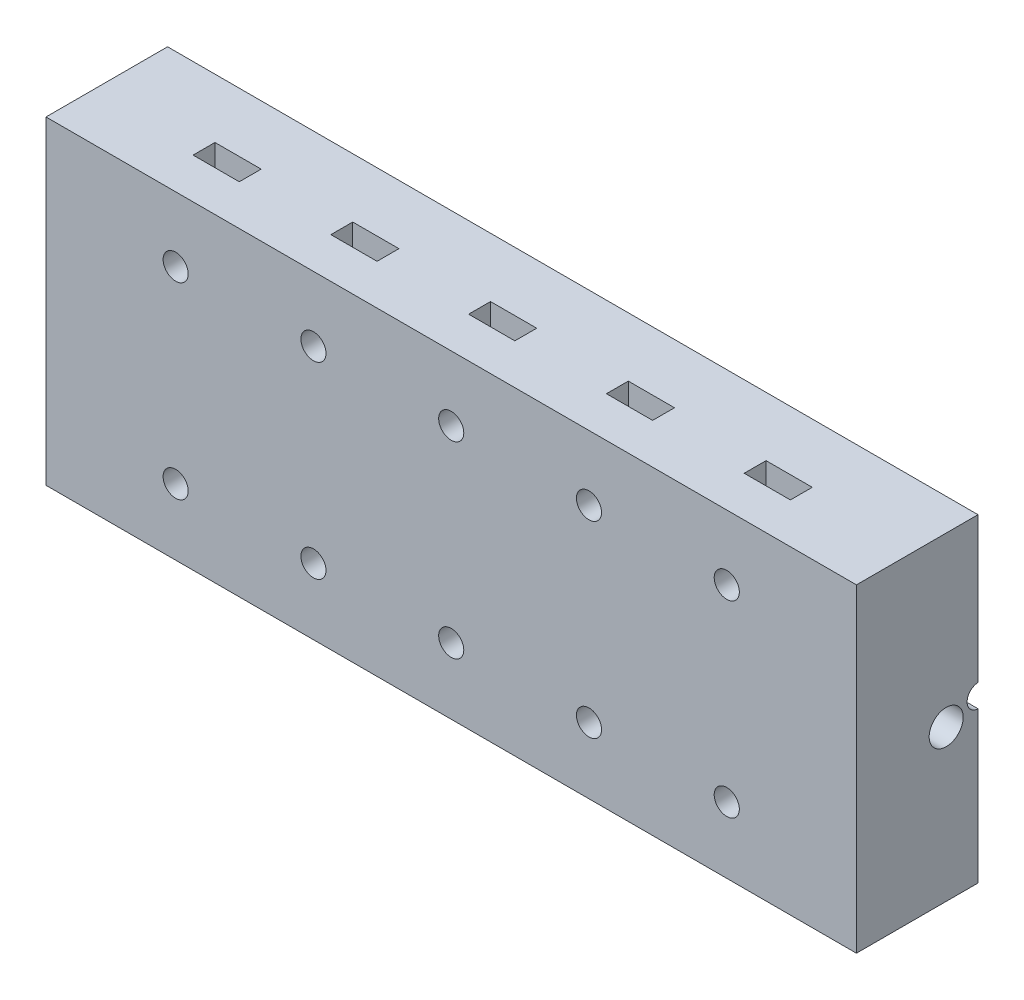
SolidWorks part; units mm, degrees
ref_plane "Ebene vorne" through (0, 0, 0) normal (0, 0, 1) x (1, 0, 0)
ref_plane "Ebene oben" through (0, 0, 0) normal (0, 1, 0) x (1, 0, 0)
ref_plane "Ebene rechts" through (0, 0, 0) normal (1, 0, 0) x (0, 0, -1)
sketch "Skizze2" plane through (0, 0, 0) normal (0, 0, 1) x (1, 0, 0)
  line L1 (0, 0) -> (100, 0)
  line L2 (0, 0) -> (0, 39.3642)
  line L3 (0, 39.3642) -> (100, 39.3642)
  line L4 (100, 0) -> (100, 39.3642)
  dimension "D1" = 39.3642
  dimension "D2" = 100
extrude "Aufsatz-Linear austragen1" add sketch "Skizze2" along normal blind 30
sketch "Skizze3" plane through (0, 0, 30) normal (0, 0, 1) x (1, 0, 0)
  line L0 (0, 19.6821) -> (100, 19.6821) construction
  line L1 (0, 39.3642) -> (0, 0) construction
  line L2 (100, 0) -> (100, 39.3642) construction
ref_plane "Ebene2" through (0, 19.7642, 0) normal (0, 1, 0) x (1, 0, 0)
sketch "Skizze9" plane through (0, 0, 30) normal (0, 0, 1) x (1, 0, 0)
  line L0 (50, 0) -> (50, 39.3642) construction
  line L1 (0, 0) -> (100, 0) construction
  line L2 (100, 39.3642) -> (0, 39.3642) construction
ref_plane "Ebene3" through (50, 0, 0) normal (-1, 0, 0) x (0, 0, 1)
sketch "Skizze10" plane through (50, 0, 0) normal (-1, 0, 0) x (0, 0, 1)
  line L0 (14.9458, 42.0451) -> (14.9458, -1.991) construction
  line L1 (-1.6741, 19.9497) -> (31.3778, 19.9497) construction
  circle A0 centre (14.9458, 20.027) radius 5
  dimension "D1" = 10
extrude "Schnitt-Linear austragen1" cut sketch "Skizze10" against normal blind 40 and the other way blind 40
ref_plane "Ebene4" through (90, 0, 0) normal (-1, 0, 0) x (0, 0, 1)
ref_plane "Ebene5" through (10, 0, 0) normal (-1, 0, 0) x (0, 0, 1)
sketch "Skizze17" plane through (90, 0, 0) normal (-1, 0, 0) x (0, 0, 1)
  circle A0 centre (14.9458, 20.027) radius 1.4
  dimension "D1" = 2.8
extrude "Schnitt-Linear austragen2" cut sketch "Skizze17" against normal through all
mirror "Spiegeln1" about plane through (50, 0, 0) normal (-1, 0, 0) of "Schnitt-Linear austragen2"
sketch "Skizze18" plane through (0, 39.3642, 0) normal (0, 1, 0) x (1, 0, 0)
  line L0 (100, -15) -> (0, -15) construction
  line L1 (100, -30) -> (100, 0) construction
ref_plane "Ebene6" through (0, 0, 15) normal (0, 0, -1) x (-1, 0, 0)
sketch "Skizze24" plane through (0, 0, 30) normal (0, 0, 1) x (1, 0, 0)
  line L0 (0, 39.3642) -> (0, 0) construction
  line L1 (100, 39.3642) -> (0, 39.3642) construction
  line L4 (100, 0) -> (100, 39.3642) construction
  circle A0 centre (16, 31.3642) radius 1.55
  circle A1 centre (33, 31.3642) radius 1.55
  circle A2 centre (50, 31.3642) radius 1.55
  circle A3 centre (67, 31.3642) radius 1.55
  circle A4 centre (84, 31.3642) radius 1.55
  dimension "D1" = 3.1
  dimension "D4" = 3.1
  dimension "D5" = 3.1
  dimension "D6" = 3.1
  dimension "D7" = 3.1
  dimension "D2" = 16
  dimension "D3" = 8
  dimension "D8" = 17
  dimension "D9" = 17
  dimension "D10" = 17
  dimension "D11" = 17
  dimension "D12" = 16
extrude "Schnitt-Linear austragen4" cut sketch "Skizze24" against normal through all
sketch "Skizze22" plane through (0, 0, 0) normal (-1, 0, 0) x (0, 0, 1)
  line L0 (30, 39.3642) -> (0, 39.3642) construction
  line L1 (0, 0) -> (15, 0)
  line L2 (0, 0) -> (0, 39.3642)
  line L3 (0, 39.3642) -> (15, 39.3642)
ref_plane "Ebene7" through (0, 0, 8.4) normal (0, 0, -1) x (-1, 0, 0)
ref_plane "Ebene8" through (16, 0, 0) normal (-1, 0, 0) x (0, 0, 1)
sketch "Skizze35" plane through (0, 0, 30) normal (0, 0, 1) x (1, 0, 0)
  line L0 (89.9018, 21.3451) -> (89.9018, 39.3769) construction
  line L1 (89.9018, 39.3769) -> (89.9018, 0) construction
  line L2 (0, 0) -> (100, 0) construction
ref_plane "Ebene9" through (90, 0, 0) normal (1, 0, 0) x (0, 0, -1)
sketch "Skizze36" plane through (90, 0, 0) normal (1, 0, 0) x (0, 0, -1)
  line L0 (-20.1004, 18.2046) -> (-18.9246, 18.6336)
  circle A0 centre (-18.9246, 18.6336) radius 0.75
  point P3 (-19.5125, 18.4191)
  dimension "D1" = 1.5
sketch "Skizze37" plane through (100, 0, 0) normal (1, 0, 0) x (0, 0, -1)
  circle A0 centre (-18.9246, 18.6336) radius 0.7369
extrude "Schnitt-Linear austragen9" cut sketch "Skizze37" against normal through all
sketch "Skizze40" plane through (100, 0, 0) normal (1, 0, 0) x (0, 0, -1)
  circle A0 centre (-18.9246, 18.6336) radius 2.1
  dimension "D1" = 4.2
extrude "Schnitt-Linear austragen10" cut sketch "Skizze40" against normal blind 6
sketch "Skizze42" plane through (0, 0, 0) normal (-1, 0, 0) x (0, 0, 1)
  line L0 (10.1439, 18.6336) -> (10.8642, 18.8426) construction
  circle A0 centre (14.9458, 20.027) radius 5 construction
  circle A1 centre (10.8642, 18.8426) radius 0.75
  dimension "D1" = 0.75
extrude "Schnitt-Linear austragen12" cut sketch "Skizze42" against normal blind 10
fillet "Verrundung1" radius 1 1 edges at (94, 18.6336, 18.1877)
sketch "Skizze46" plane through (0, 0, 0) normal (0, 0, -1) x (-1, 0, 0)
  circle A0 centre (-84, 31.3642) radius 2.85
  dimension "D1" = 5.7
extrude "Schnitt-Linear austragen15" cut sketch "Skizze46" against normal blind 10
sketch "Skizze50" plane through (0, 0, 30) normal (0, 0, 1) x (1, 0, 0)
  line L0 (81.15, 33.0096) -> (81.15, 39.3642)
  line L2 (81.15, 33.0096) -> (81.15, 29.7187)
  line L3 (81.15, 29.7187) -> (84, 28.0733)
  line L4 (84, 28.0733) -> (86.85, 29.7187)
  line L5 (86.85, 29.7187) -> (86.85, 33.0096)
  line L7 (100, 39.3642) -> (0, 39.3642) construction
  line L8 (81.15, 39.3642) -> (86.85, 39.3642)
  line L9 (86.85, 39.3642) -> (86.85, 33.0096)
  line L11 (84, 34.6551) -> (81.15, 33.0096) [skipped]
  line L12 (86.85, 33.0096) -> (84, 34.6551) [skipped]
  circle A0 centre (84, 31.3642) radius 2.85 construction
  dimension "D1" = 5.7
extrude "Schnitt-Linear austragen25" cut sketch "Skizze50" against normal blind 2.7 from offset 5 offset against normal yes
pattern_linear "Lineares Muster1" count 5 spacing 17 along (-1, 0, 0) of "Schnitt-Linear austragen25", "Schnitt-Linear austragen15"
mirror "Spiegeln2" about plane through (0, 19.7642, 0) normal (0, 1, 0) of "Lineares Muster1", "Schnitt-Linear austragen15", "Schnitt-Linear austragen25"
mirror "Spiegeln3" about plane through (0, 19.7642, 0) normal (0, 1, 0) of "Schnitt-Linear austragen4"
sketch "Skizze45" plane through (100, 0, 0) normal (1, 0, 0) x (0, 0, -1)
  line L1 (-15, 39.3642) -> (0, 39.3642)
  line L2 (-15, 39.3642) -> (-15, 0)
  line L3 (-15, 0) -> (0, 0)
  line L4 (0, 39.3642) -> (0, 0)
extrude "Schnitt-Linear austragen14" cut sketch "Skizze45" against normal blind 100
